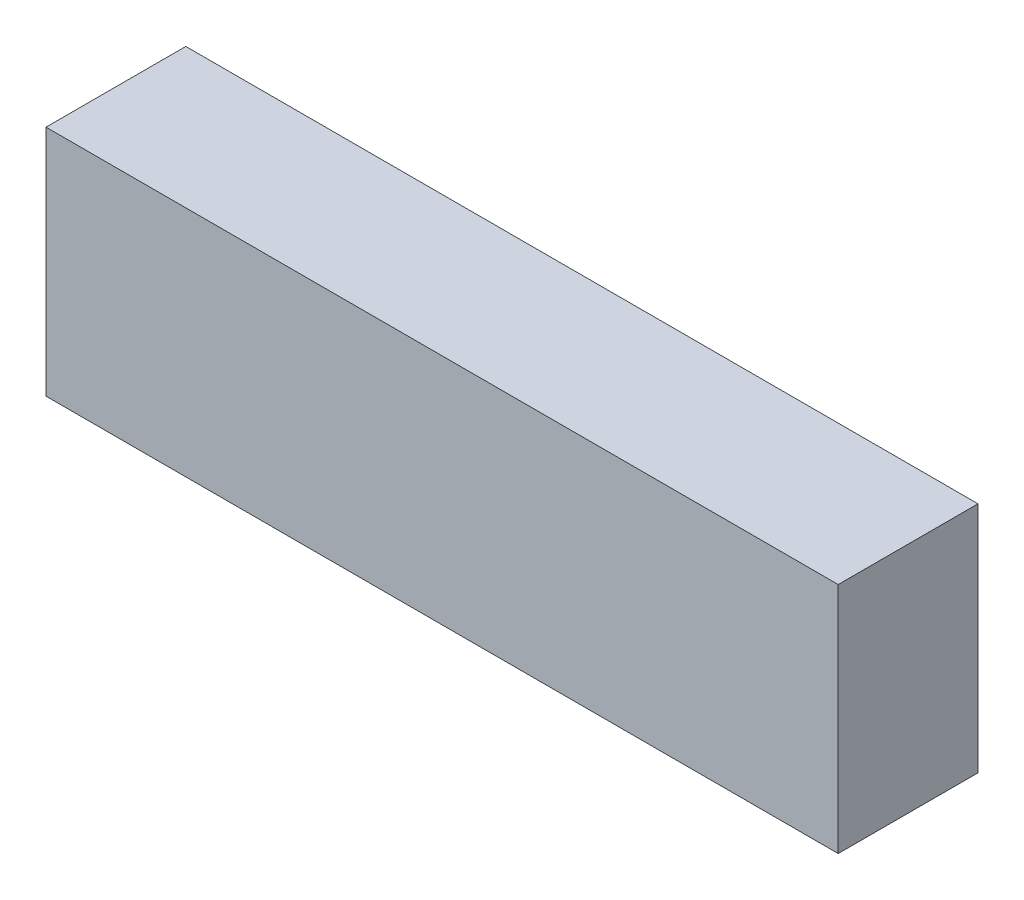
SolidWorks part; units mm, degrees
ref_plane "Alzado" through (0, 0, 0) normal (0, 0, 1) x (1, 0, 0)
ref_plane "Planta" through (0, 0, 0) normal (0, 1, 0) x (1, 0, 0)
ref_plane "Vista lateral" through (0, 0, 0) normal (1, 0, 0) x (0, 0, -1)
sketch "Croquis2" plane through (0, 0, 3.1716) normal (0, 0, 1) x (1, 0, 0)
  line L1 (491.8348, 1149.027) -> (1341.8348, 1149.027)
  line L2 (491.8348, 1149.027) -> (491.8348, 899.027)
  line L3 (491.8348, 899.027) -> (1341.8348, 899.027)
  line L4 (1341.8348, 1149.027) -> (1341.8348, 899.027)
  dimension "D1" = 850
  dimension "D2" = 250
extrude "Saliente-Extruir1" add sketch "Croquis2" along normal blind 150
sketch "Croquis3" plane through (0, 0, 3.1716) normal (0, 0, -1) x (-1, 0, 0)
  line L0 (-1341.8348, 1149.027) -> (-491.8348, 1149.027) construction
  line L1 (-491.8348, 1149.027) -> (-491.8348, 899.027) construction
  circle A0 centre (-616.8348, 1024.027) radius 75
  point P2 (-614.0858, 1033.9758)
  dimension "D1" = 150
  dimension "D2" = 125
  dimension "D3" = 125
extrude "Cortar-Extruir1" cut sketch "Croquis3" against normal blind 50
